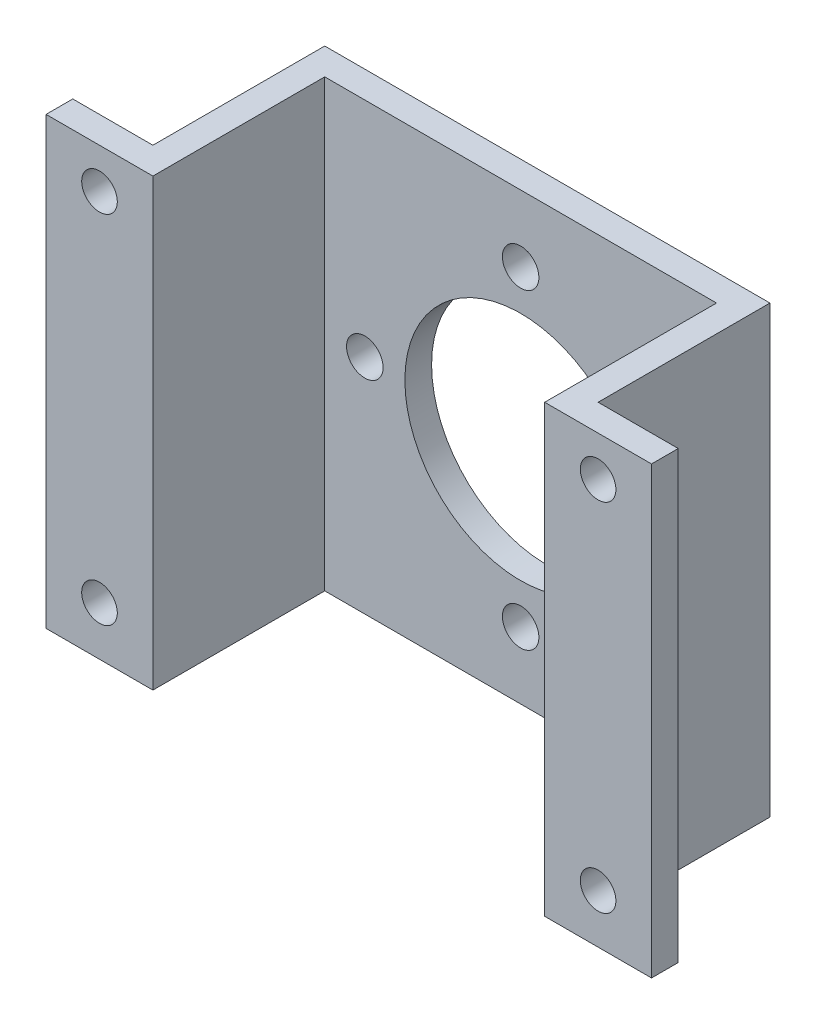
SolidWorks part; units mm, degrees
ref_plane "Front" through (0, 0, 0) normal (0, 0, 1) x (1, 0, 0)
ref_plane "Top" through (0, 0, 0) normal (0, 1, 0) x (1, 0, 0)
ref_plane "Right" through (0, 0, 0) normal (1, 0, 0) x (0, 0, -1)
sketch "草图2" plane through (0, 0, 0) normal (0, 1, 0) x (1, 0, 0)
  line L0 (-22, -19.3) -> (-22, 0)
  line L1 (-22, 0) -> (22, 0)
  line L2 (22, -19.3) -> (34, -19.3)
  line L3 (-34, -16.3) -> (-25, -16.3)
  line L4 (-25, -16.3) -> (-25, 3)
  line L5 (-25, 3) -> (25, 3)
  line L6 (-34, -19.3) -> (-22, -19.3)
  line L7 (22, 0) -> (22, -19.3)
  line L8 (25, 3) -> (25, -16.3)
  line L9 (25, -16.3) -> (34, -16.3)
  line L10 (-34, -16.3) -> (-34, -19.3)
  line L11 (34, -16.3) -> (34, -19.3)
  point P2 (0, 0)
  dimension "D1" = 44
  dimension "D2" = 68
  dimension "D3" = 19.3
  dimension "D4" = 3
extrude "凸台-拉伸1" add sketch "草图2" along normal mid plane 50
sketch "草图3" plane through (0, 0, -3) normal (0, 0, -1) x (-1, 0, 0)
  circle A0 centre (0, 0) radius 13
  circle A1 centre (0, 0) radius 17.5 construction
  circle A2 centre (0, 17.5) radius 2.05
  circle A3 centre (-17.5, 0) radius 2.05
  circle A4 centre (17.5, 0) radius 2.05
  circle A5 centre (0, -17.5) radius 2.05
  dimension "D1" = 26
  dimension "D2" = 35
  dimension "D3" = 4.1
extrude "切除-拉伸1" cut sketch "草图3" against normal blind 50
sketch "草图4" plane through (0, 0, 16.3) normal (0, 0, -1) x (-1, 0, 0)
  circle A4 centre (28, 20.5) radius 2
  circle A5 centre (28, -19.5) radius 2
  circle A6 centre (-28, 20.5) radius 2
  circle A7 centre (-28, -19.5) radius 2
extrude "切除-拉伸2" cut sketch "草图4" against normal blind 10
